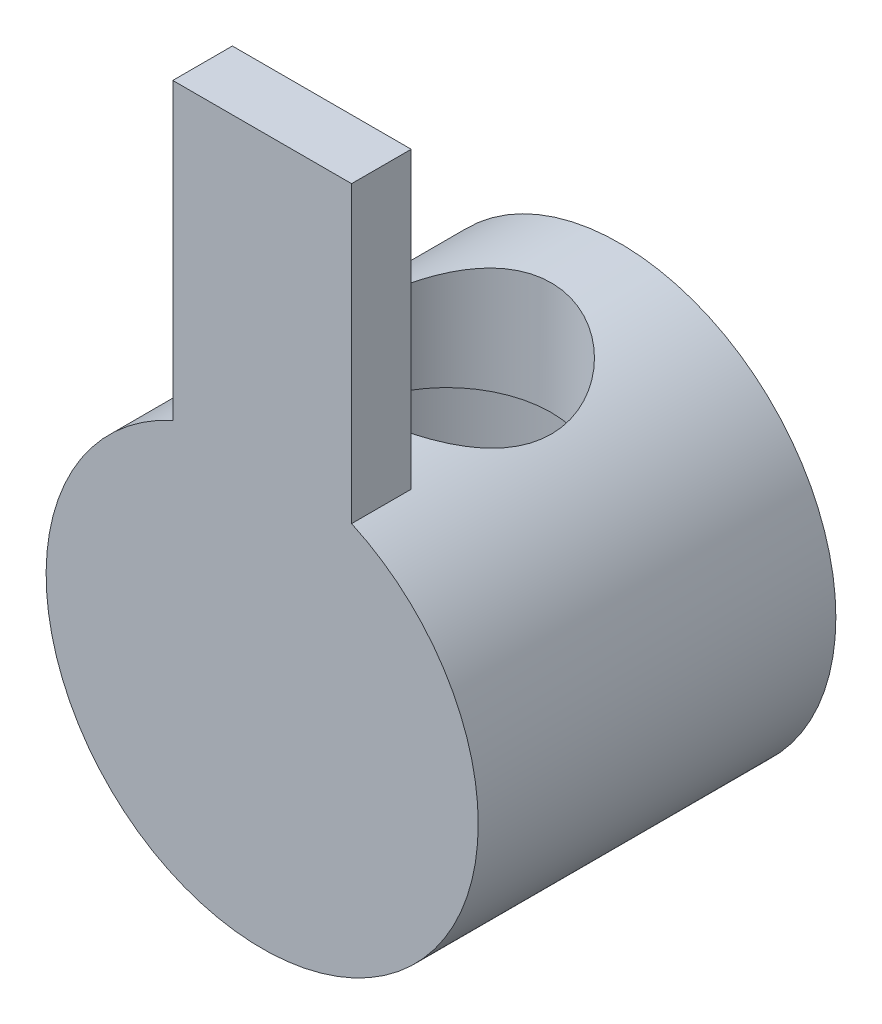
SolidWorks part; units mm, degrees
ref_plane "前视基准面" through (0, 0, 0) normal (0, 0, 1) x (1, 0, 0)
ref_plane "上视基准面" through (0, 0, 0) normal (0, 1, 0) x (1, 0, 0)
ref_plane "右视基准面" through (0, 0, 0) normal (1, 0, 0) x (0, 0, -1)
sketch "草图1" plane through (0, 0, 0) normal (0, 0, 1) x (1, 0, 0)
  line L1 (-3, -11.5) -> (3, -11.5)
  line L2 (-3, -11.5) -> (-3, 11.5)
  line L3 (-3, 11.5) -> (3, 11.5)
  line L4 (3, -11.5) -> (3, 11.5)
  line L5 (-3, -11.5) -> (3, 11.5) construction
  line L6 (-3, 11.5) -> (3, -11.5) construction
  point P0 (0, 0)
  dimension "D1" = 6
  dimension "D2" = 23
extrude "凸台-拉伸1" add sketch "草图1" along normal blind 2
sketch "草图4" plane through (0, 0, 0) normal (0, 0, -1) x (-1, 0, 0)
  line L0 (3, 11.5) -> (3, -11.5) construction
  line L1 (-3, -11.5) -> (3, -11.5)
  line L2 (-3, -11.5) -> (-3, -7.0516)
  line L3 (-3, -7.0516) -> (3, -7.0516)
  line L4 (3, -11.5) -> (3, -7.0516)
extrude "切除-拉伸1" cut sketch "草图4" against normal through all
sketch "草图2" plane through (0, 0, 2) normal (0, 0, 1) x (1, 0, 0)
  circle A0 centre (0, -4.98) radius 7.25
  dimension "D1" = 14.5
extrude "凸台-拉伸2" add sketch "草图2" against normal blind 12
sketch "草图5" plane through (0, 11.5, 0) normal (0, 1, 0) x (1, 0, 0)
  line L0 (0, -2) -> (0, 10) construction
  line L1 (3, -2) -> (-3, -2) construction
  line L2 (7.25, 10) -> (-7.25, 10) construction
  circle A0 centre (0, 4.2) radius 3.5
  dimension "D1" = 7
  dimension "D2" = 6.2
extrude "切除-拉伸2" cut sketch "草图5" against normal through all
ref_plane "基准面1" through (0, -14.23, 0) normal (0, 1, 0) x (-1, 0, 0)
ref_plane "基准面2" through (0, -4.25, 0) normal (0, 1, 0) x (1, 0, 0)
sketch "草图6" plane through (0, -4.25, 0) normal (0, 1, 0) x (1, 0, 0)
  circle A0 centre (0, 4.2) radius 5
extrude "切除-拉伸3" cut sketch "草图6" against normal blind 10 and the other way blind 2.75
